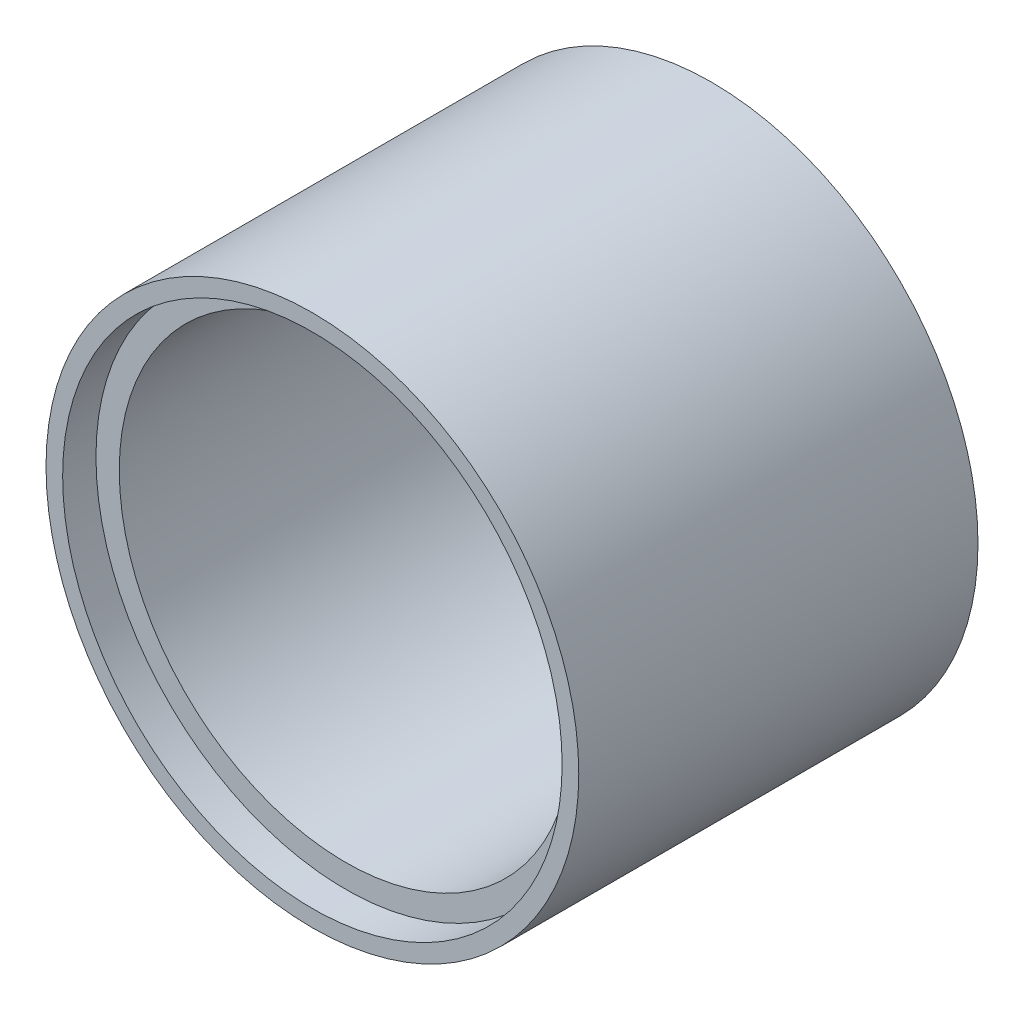
SolidWorks part; units mm, degrees
ref_plane "Front Plane" through (0, 0, 0) normal (0, 0, 1) x (1, 0, 0)
ref_plane "Top Plane" through (0, 0, 0) normal (0, 1, 0) x (1, 0, 0)
ref_plane "Right Plane" through (0, 0, 0) normal (1, 0, 0) x (0, 0, -1)
sketch "Sketch1" plane through (0, 0, 0) normal (0, 1, 0) x (1, 0, 0)
  line L0 (0, 51.376) -> (0, -57.9079) construction
  line L1 (-47.7332, 0) -> (48.4869, 0) construction
  line L2 (-34, 24.9747) -> (-34, -24.9747)
  line L3 (-34, -24.9747) -> (-37.5, -24.9747)
  line L4 (-37.5, -24.9747) -> (-37.5, -29.9747)
  line L5 (-37.5, -29.9747) -> (-40, -29.9747)
  line L6 (-40, -29.9747) -> (-40, 29.9747)
  line L7 (-37.5, 29.9747) -> (-40, 29.9747)
  line L8 (-37.5, 24.9747) -> (-37.5, 29.9747)
  line L9 (-34, 24.9747) -> (-37.5, 24.9747)
  point P6 (-40, 0)
  point P12 (-34, 0)
  dimension "D1" = 68
  dimension "D2" = 80
  dimension "D3" = 2.5
  dimension "D4" = 5
  dimension "D5" = 75
revolve "Revolve1" add sketch "Sketch1" angle 360 about L0
